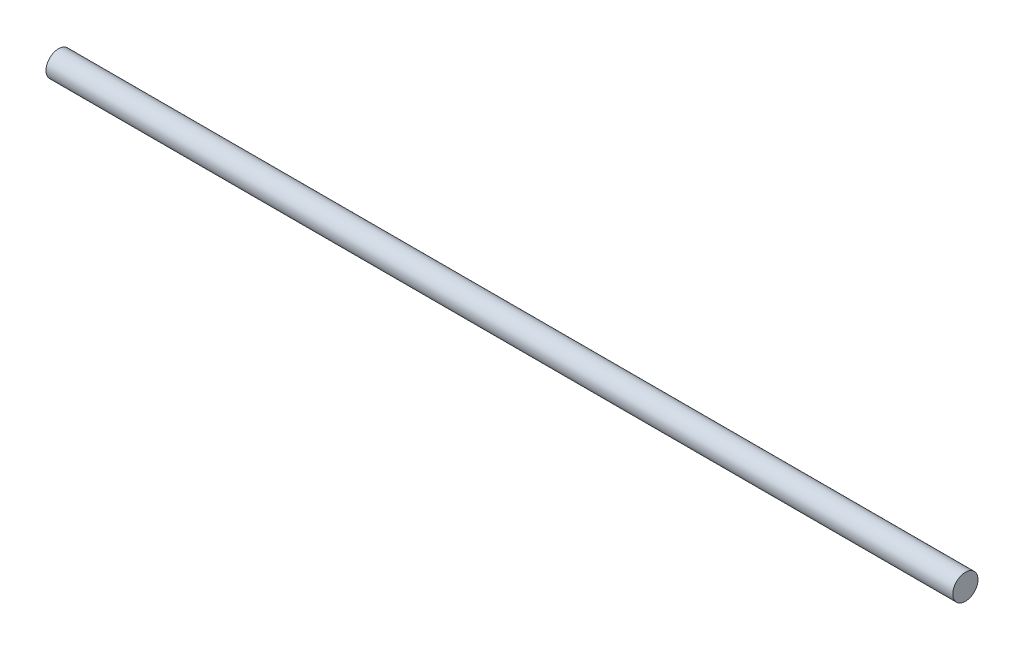
SolidWorks part; units mm, degrees
ref_plane "Front Plane" through (0, 0, 0) normal (0, 0, 1) x (1, 0, 0)
ref_plane "Top Plane" through (0, 0, 0) normal (0, 1, 0) x (1, 0, 0)
ref_plane "Right Plane" through (0, 0, 0) normal (1, 0, 0) x (0, 0, -1)
sketch "Sketch1" plane through (0, 0, 0) normal (1, 0, 0) x (0, 0, -1)
  circle A0 centre (0, 0) radius 3.175
  dimension "D1" = 6.35
extrude "Boss-Extrude2" add sketch "Sketch1" along normal blind 228.6
